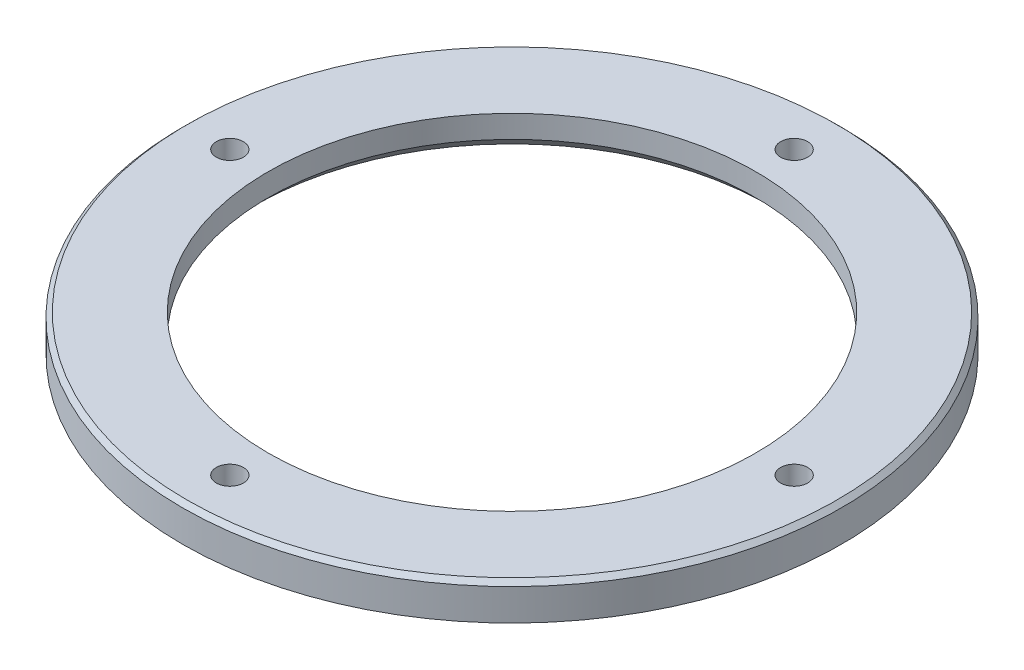
SolidWorks part; units mm, degrees
ref_plane "Спереди" through (0, 0, 0) normal (0, 0, 1) x (1, 0, 0)
ref_plane "Сверху" through (0, 0, 0) normal (0, 1, 0) x (1, 0, 0)
ref_plane "Справа" through (0, 0, 0) normal (1, 0, 0) x (0, 0, -1)
sketch "Эскиз1" plane through (0, 0, 0) normal (0, 1, 0) x (1, 0, 0)
  circle A0 centre (0, 0) radius 54
  circle A1 centre (0, 0) radius 73
  dimension "D1" = 108
  dimension "D2" = 146
extrude "Бобышка-Вытянуть1" add sketch "Эскиз1" along normal blind 8
sketch "Эскиз2" plane through (0, 8, 0) normal (0, 1, 0) x (-1, 0, 0)
  line L0 (0, -73) -> (0, 62.5) construction
  line L1 (0, 62.5) -> (-62.5, 0) construction
  line L2 (-62.5, 0) -> (62.5, 0) construction
  circle A0 centre (0, 0) radius 62.5 construction
  circle A1 centre (0, 0) radius 73 construction
  circle A2 centre (62.5, 0) radius 3
  circle A3 centre (0, -62.5) radius 3
  circle A4 centre (0, 62.5) radius 3
  circle A5 centre (-62.5, 0) radius 3
  dimension "D1" = 125
  dimension "D2" = 6
  dimension "D3" = 6
  dimension "D4" = 6
  dimension "D5" = 6
extrude "Вырез-Вытянуть1" cut sketch "Эскиз2" against normal blind 10
chamfer "Фаска1" distance 1 angle 45 1 edges at (0, 8, 73)
chamfer "Фаска2" distance 3 angle 45 1 edges at (0, 0, 54)
